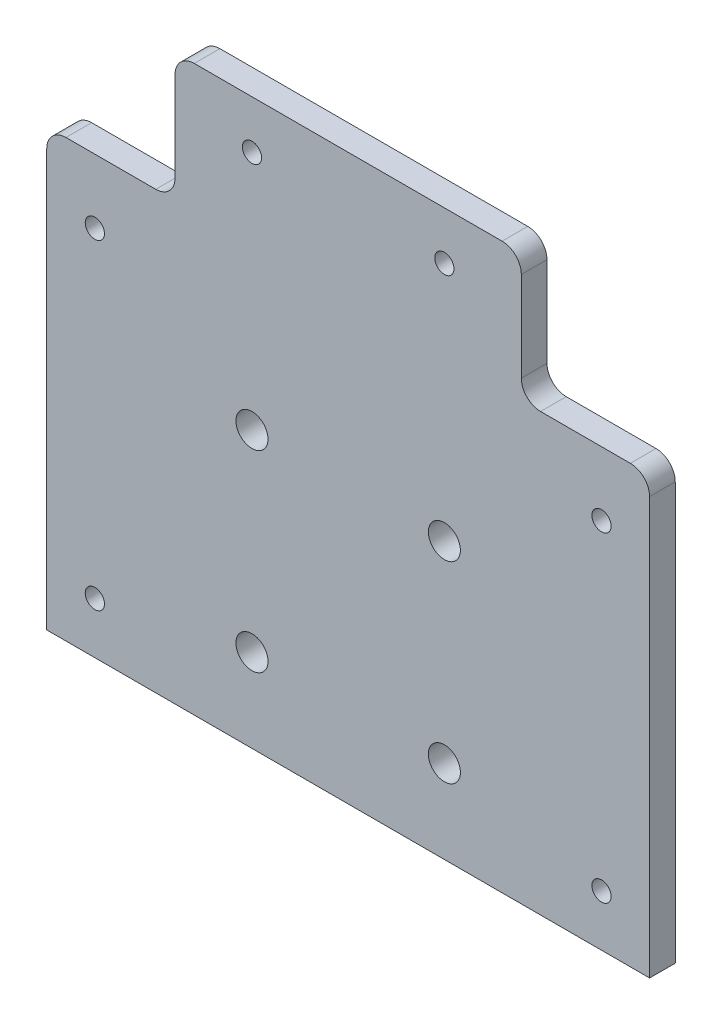
SolidWorks part; units mm, degrees
material "A-玻璃纤维"
ref_plane "前视基准面" through (0, 0, 0) normal (0, 0, 1) x (1, 0, 0)
ref_plane "上视基准面" through (0, 0, 0) normal (0, 1, 0) x (1, 0, 0)
ref_plane "右视基准面" through (0, 0, 0) normal (1, 0, 0) x (0, 0, -1)
sketch "草图1" plane through (0, 0, 0) normal (0, 0, 1) x (1, 0, 0)
  line L1 (-47, 44) -> (47, 44)
  line L2 (-47, 44) -> (-47, -44)
  line L3 (-47, -44) -> (47, -44)
  line L4 (47, 44) -> (47, -44)
  line L5 (-47, 44) -> (47, -44) construction
  line L6 (-47, -44) -> (47, 44) construction
  point P0 (0, 0)
  dimension "D1" = 94
  dimension "D2" = 88
extrude "凸台-拉伸1" add sketch "草图1" along normal blind 4
sketch "草图2" plane through (0, 0, 4) normal (0, 0, 1) x (1, 0, 0)
  line L0 (0, 44) -> (0, -44) construction
  line L1 (-47, 44) -> (-27, 44)
  line L2 (-47, 44) -> (-47, 24)
  line L3 (-47, 24) -> (-27, 24)
  line L4 (-27, 44) -> (-27, 24)
  line L5 (47, 44) -> (-47, 44) construction
  line L6 (-47, -44) -> (47, -44) construction
  line L7 (27, 44) -> (27, 24)
  line L8 (47, 24) -> (27, 24)
  line L9 (47, 44) -> (47, 24)
  line L10 (47, 44) -> (27, 44)
  dimension "D1" = 20
  dimension "D2" = 20
extrude "切除-拉伸1" cut sketch "草图2" against normal through all
fillet "圆角1" radius 3 6 edges at (47, 24, 2) (-47, 24, 2) (-27, 44, 2) (27, 44, 2) (27, 24, 2) (-27, 24, 2)
sketch "草图3" plane through (0, 0, 4) normal (0, 0, 1) x (1, 0, 0)
  line L0 (0, 44) -> (0, -44) construction
  line L1 (24, 44) -> (-24, 44) construction
  line L2 (-47, -44) -> (47, -44) construction
  line L3 (0, 44) -> (0, -44) construction
  line L5 (-15, -1) -> (15, -1) construction
  line L6 (-15, -1) -> (-15, -31) construction
  line L7 (-15, -31) -> (15, -31) construction
  line L8 (15, -1) -> (15, -31) construction
  line L9 (-15, -1) -> (15, -31) construction
  line L10 (-15, -31) -> (15, -1) construction
  circle A0 centre (-15, -1) radius 2.5
  circle A1 centre (15, -1) radius 2.5
  circle A2 centre (15, -31) radius 2.5
  circle A3 centre (-15, -31) radius 2.5
  point P8 (0, -16)
  dimension "D4" = 5
  dimension "D1" = 30
  dimension "D2" = 0
  dimension "D3" = 60
extrude "切除-拉伸2" cut sketch "草图3" against normal through all
sketch "草图4" plane through (0, 0, 4) normal (0, 0, 1) x (1, 0, 0)
  line L0 (-27, 36.5) -> (27, 36.5) construction
  line L1 (-27, 27) -> (-27, 41) construction
  line L2 (27, 41) -> (27, 27) construction
  line L3 (39.5, 24) -> (39.5, -44) construction
  line L4 (30, 24) -> (44, 24) construction
  line L5 (-47, -44) -> (47, -44) construction
  line L6 (0, -44) -> (0, 44) construction
  line L7 (24, 44) -> (-24, 44) construction
  line L8 (47, -44) -> (47, 21) construction
  circle A0 centre (-15, 36.5) radius 1.5
  circle A2 centre (39.5, 14) radius 1.5
  circle A3 centre (39.5, -36) radius 1.5
  circle A4 centre (15, 36.5) radius 1.5
  circle A5 centre (-39.5, -36) radius 1.5
  circle A6 centre (-39.5, 14) radius 1.5
  dimension "D3" = 3
  dimension "D5" = 30
  dimension "D1" = 7.5
  dimension "D2" = 7.5
  dimension "D4" = 15
  dimension "D6" = 50
extrude "切除-拉伸3" cut sketch "草图4" against normal through all
